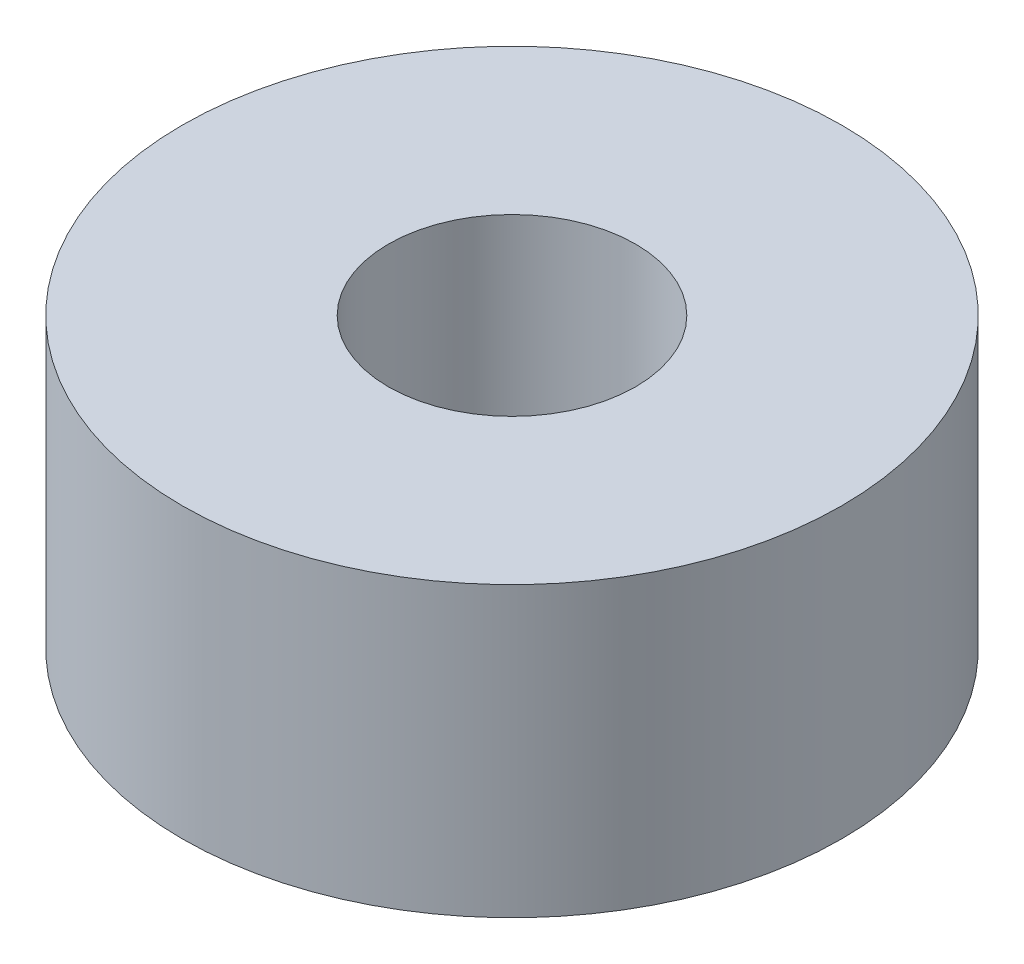
SolidWorks part; units mm, degrees
material "AISI 304"
ref_plane "前视基准面" through (0, 0, 0) normal (0, 0, 1) x (1, 0, 0)
ref_plane "上视基准面" through (0, 0, 0) normal (0, 1, 0) x (1, 0, 0)
ref_plane "右视基准面" through (0, 0, 0) normal (1, 0, 0) x (0, 0, -1)
other "Configuration Table"
sketch "草图1" plane through (0, 0, 0) normal (0, 1, 0) x (1, 0, 0)
  circle A0 centre (0, 0) radius 1.5
  circle A1 centre (0, 0) radius 4
  dimension "D1" = 3
  dimension "D2" = 8
extrude "凸台-拉伸1" add sketch "草图1" along normal blind 3.5
